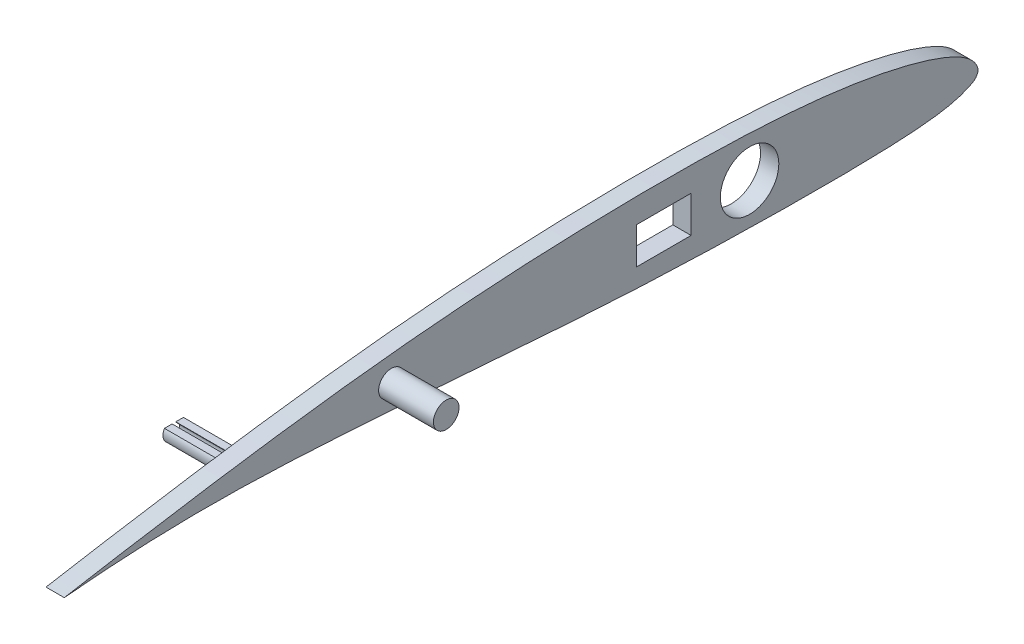
SolidWorks part; units mm, degrees
material "ABS generico"
ref_plane "Piano frontale" through (0, 0, 0) normal (0, 0, 1) x (1, 0, 0)
ref_plane "Piano superiore" through (0, 0, 0) normal (0, 1, 0) x (1, 0, 0)
ref_plane "Piano destro" through (0, 0, 0) normal (1, 0, 0) x (0, 0, -1)
curve "Curva1"
  spline degree 3 poles (0, 0.1724, 248.285) (0, -0.053, 250.4273) (0, 0.2462, 248.3284) (0, 0.5529, 246.6445) (0, 1.2459, 242.6221) (0, 2.0989, 237.7464) (0, 3.1818, 231.3634) (0, 4.2933, 223.9772) (0, 5.7312, 215.5604) (0, 7.1315, 206.3004) (0, 8.6324, 196.1631) (0, 10.1162, 185.3524) (0, 11.5493, 173.9891) (0, 12.8816, 162.1914) (0, 14.0593, 150.0724) (0, 15.0523, 137.7438) (0, 15.8256, 125.3116) (0, 16.3834, 112.8888) (0, 16.7267, 100.597) (0, 16.8648, 88.5669) (0, 16.792, 76.9314) (0, 16.4941, 65.8165) (0, 15.9609, 55.3329) (0, 15.1594, 45.573) (0, 14.0978, 36.6074) (0, 12.7884, 28.4972) (0, 11.2839, 21.2988) (0, 9.6413, 15.0749) (0, 7.9136, 9.8809) (0, 6.1182, 5.7699) (0, 4.2384, 2.7289) (0, 2.3057, 0.8126) (0, 0.7927, 0.0312) (0, -0.4105, -0.0213) (0, -1.7115, 0.4949) (0, -2.8658, 2.6253) (0, -4.0404, 5.6977) (0, -4.9287, 10.0719) (0, -5.5974, 15.6262) (0, -6.0122, 22.4122) (0, -6.265, 30.3619) (0, -6.3814, 39.3972) (0, -6.3554, 49.3987) (0, -6.2185, 60.2453) (0, -5.9476, 71.8018) (0, -5.5368, 83.9408) (0, -4.9386, 96.5461) (0, -4.1527, 109.5201) (0, -3.2196, 122.7671) (0, -2.1909, 136.1764) (0, -1.148, 149.6158) (0, -0.1602, 162.9314) (0, 0.706, 175.9537) (0, 1.3896, 188.4999) (0, 1.8332, 200.3712) (0, 1.9676, 211.3376) (0, 1.8232, 221.1842) (0, 1.4973, 229.6804) (0, 1.0741, 236.8065) (0, 0.6857, 242.1894) (0, 0.3087, 246.5181) (0, 0.1724, 248.285) (0, -0.053, 250.4273) (0, 0.2462, 248.3284) knots -0.014202 -0.006329 -0.001589 0 0.001576 0.006211 0.01368 0.023764 0.036307 0.051658 0.068045 0.086769 0.107053 0.128647 0.151303 0.174786 0.19886 0.223309 0.247929 0.272522 0.296848 0.320648 0.343669 0.365658 0.3864 0.405741 0.423561 0.439779 0.454311 0.467034 0.477831 0.486643 0.493542 0.498786 0.50271 0.50309 0.505896 0.510322 0.516831 0.525521 0.536535 0.549945 0.565696 0.583577 0.603379 0.624844 0.647727 0.671743 0.696673 0.722357 0.748609 0.77521 0.801891 0.828329 0.854175 0.879074 0.902636 0.924421 0.943939 0.960827 0.974827 0.985798 0.993671 0.998411 1 1.001576 1.006211 1.01368 periodic
sketch "Schizzo1" plane through (0, 0, 0) normal (1, 0, 0) x (0, 0, -1)
  line L0 (-250, 0) -> (0.0001, 0.0174) construction
  line L1 (0.0001, 0.0174) -> (-0.0034, 50.0174) construction
  line L2 (-62.4999, 16.3096) -> (-62.4999, -6.155) construction
  line L4 (-78.4999, 10.0773) -> (-93.4999, 10.0773)
  line L5 (-78.4999, 10.0773) -> (-78.4999, 0.0773)
  line L6 (-78.4999, 0.0773) -> (-93.4999, 0.0773)
  line L7 (-93.4999, 10.0773) -> (-93.4999, 0.0773)
  circle A0 centre (-62.4999, 5.0773) radius 8
  spline S0 degree 3 poles (-248.3284, 0.2462) (-250.4273, -0.053) (-248.285, 0.1724) (-246.5181, 0.3087) (-242.1894, 0.6857) (-236.8065, 1.0741) (-229.6804, 1.4973) (-221.1842, 1.8232) (-211.3376, 1.9676) (-200.3712, 1.8332) (-188.4999, 1.3896) (-175.9537, 0.706) (-162.9314, -0.1602) (-149.6158, -1.148) (-136.1764, -2.1909) (-122.7671, -3.2196) (-109.5201, -4.1527) (-96.5461, -4.9386) (-83.9408, -5.5368) (-71.8018, -5.9476) (-60.2453, -6.2185) (-49.3987, -6.3554) (-39.3972, -6.3814) (-30.3619, -6.265) (-22.4122, -6.0122) (-15.6262, -5.5974) (-10.0719, -4.9287) (-5.6977, -4.0404) (-2.6253, -2.8658) (-0.4949, -1.7115) (0.0213, -0.4105) (-0.0312, 0.7927) (-0.8126, 2.3057) (-2.7289, 4.2384) (-5.7699, 6.1182) (-9.8809, 7.9136) (-15.0749, 9.6413) (-21.2988, 11.2839) (-28.4972, 12.7884) (-36.6074, 14.0978) (-45.573, 15.1594) (-55.3329, 15.9609) (-65.8165, 16.4941) (-76.9314, 16.792) (-88.5669, 16.8648) (-100.597, 16.7267) (-112.8888, 16.3834) (-125.3116, 15.8256) (-137.7438, 15.0523) (-150.0724, 14.0593) (-162.1914, 12.8816) (-173.9891, 11.5493) (-185.3524, 10.1162) (-196.1631, 8.6324) (-206.3004, 7.1315) (-215.5604, 5.7312) (-223.9772, 4.2933) (-231.3634, 3.1818) (-237.7464, 2.0989) (-242.6221, 1.2459) (-246.6445, 0.5529) (-248.3284, 0.2462) (-250.4273, -0.053) (-248.285, 0.1724) knots -0.01368 -0.006211 -0.001576 0 0.001589 0.006329 0.014202 0.025173 0.039173 0.056061 0.075579 0.097364 0.120926 0.145825 0.171671 0.198109 0.22479 0.251391 0.277643 0.303327 0.328257 0.352273 0.375156 0.396621 0.416423 0.434304 0.450055 0.463465 0.474479 0.483169 0.489678 0.494104 0.49691 0.49729 0.501214 0.506458 0.513357 0.522169 0.532966 0.545689 0.560221 0.576439 0.594259 0.6136 0.634342 0.656331 0.679352 0.703152 0.727478 0.752071 0.776691 0.80114 0.825214 0.848697 0.871353 0.892947 0.913231 0.931955 0.948342 0.963693 0.976236 0.98632 0.993789 0.998424 1 1.001589 1.006329 1.014202 only from (-250, 0) to (-250, 0) construction
  spline S1 degree 3 poles (-248.3284, 0.2462) (-250.4273, -0.053) (-248.285, 0.1724) (-246.5181, 0.3087) (-242.1894, 0.6857) (-236.8065, 1.0741) (-229.6804, 1.4973) (-221.1842, 1.8232) (-211.3376, 1.9676) (-200.3712, 1.8332) (-188.4999, 1.3896) (-175.9537, 0.706) (-162.9314, -0.1602) (-149.6158, -1.148) (-136.1764, -2.1909) (-122.7671, -3.2196) (-109.5201, -4.1527) (-96.5461, -4.9386) (-83.9408, -5.5368) (-71.8018, -5.9476) (-60.2453, -6.2185) (-49.3987, -6.3554) (-39.3972, -6.3814) (-30.3619, -6.265) (-22.4122, -6.0122) (-15.6262, -5.5974) (-10.0719, -4.9287) (-5.6977, -4.0404) (-2.6253, -2.8658) (-0.4949, -1.7115) (0.0213, -0.4105) (-0.0312, 0.7927) (-0.8126, 2.3057) (-2.7289, 4.2384) (-5.7699, 6.1182) (-9.8809, 7.9136) (-15.0749, 9.6413) (-21.2988, 11.2839) (-28.4972, 12.7884) (-36.6074, 14.0978) (-45.573, 15.1594) (-55.3329, 15.9609) (-65.8165, 16.4941) (-76.9314, 16.792) (-88.5669, 16.8648) (-100.597, 16.7267) (-112.8888, 16.3834) (-125.3116, 15.8256) (-137.7438, 15.0523) (-150.0724, 14.0593) (-162.1914, 12.8816) (-173.9891, 11.5493) (-185.3524, 10.1162) (-196.1631, 8.6324) (-206.3004, 7.1315) (-215.5604, 5.7312) (-223.9772, 4.2933) (-231.3634, 3.1818) (-237.7464, 2.0989) (-242.6221, 1.2459) (-246.6445, 0.5529) (-248.3284, 0.2462) (-250.4273, -0.053) (-248.285, 0.1724) knots -0.01368 -0.006211 -0.001576 0 0.001589 0.006329 0.014202 0.025173 0.039173 0.056061 0.075579 0.097364 0.120926 0.145825 0.171671 0.198109 0.22479 0.251391 0.277643 0.303327 0.328257 0.352273 0.375156 0.396621 0.416423 0.434304 0.450055 0.463465 0.474479 0.483169 0.489678 0.494104 0.49691 0.49729 0.501214 0.506458 0.513357 0.522169 0.532966 0.545689 0.560221 0.576439 0.594259 0.6136 0.634342 0.656331 0.679352 0.703152 0.727478 0.752071 0.776691 0.80114 0.825214 0.848697 0.871353 0.892947 0.913231 0.931955 0.948342 0.963693 0.976236 0.98632 0.993789 0.998424 1 1.001589 1.006329 1.014202 only from (-250, 0) to (-250, 0)
  point P11 (-78.4999, 5.0773)
  dimension "D3" = 16
  dimension "D1" = 50
  dimension "D2" = 62.5
  dimension "D4" = 15
  dimension "D5" = 10
  dimension "D6" = 16
extrude "CorpoFoam" add sketch "Schizzo1" along normal blind 5
sketch "Schizzo2" plane through (0, 0, 0) normal (-1, 0, 0) x (0, 0, 1)
  circle A0 centre (160.4999, 6.0773) radius 3.5
  circle A1 centre (62.4999, 5.0773) radius 8 construction
  dimension "D1" = 7
  dimension "D2" = 98
  dimension "D3" = 1
extrude "PernoAggancio" add sketch "Schizzo2" against normal blind 20
sketch "Schizzo3" plane through (5, 0, 0) normal (1, 0, 0) x (0, 0, -1)
  line L0 (-200, 8.0593) -> (-200, 1.7757) construction
  line L1 (-200.5, 6.4175) -> (-199.5, 3.4175) construction
  line L2 (-197.4019, 6.4175) -> (-199.5, 6.4175)
  line L4 (-197.4019, 3.4175) -> (-199.5, 3.4175)
  line L7 (-200.5, 6.4175) -> (-200.5, 6.3317)
  line L9 (-199.5, 6.4175) -> (-199.5, 6.3317)
  line L10 (-199.5, 6.4175) -> (-200.5, 3.4175) construction
  line L11 (-200.5, 6.4175) -> (-202.5981, 6.4175)
  line L12 (-200.5, 3.4175) -> (-202.5981, 3.4175)
  line L13 (-199.5, 3.5033) -> (-199.5, 3.4175)
  line L14 (-200.5, 3.5033) -> (-200.5, 3.4175)
  arc A0 (-200.5, 6.3317) -> (-200.5, 3.5033) centre (-200, 4.9175) ccw
  arc A1 (-202.5981, 6.4175) -> (-202.5981, 3.4175) centre (-200, 4.9175) ccw
  arc A2 (-197.4019, 3.4175) -> (-197.4019, 6.4175) centre (-200, 4.9175) ccw
  arc A3 (-199.5, 3.5033) -> (-199.5, 6.3317) centre (-200, 4.9175) ccw
  spline S0 degree 3 poles (-248.3284, 0.2462) (-250.4273, -0.053) (-248.285, 0.1724) (-246.5181, 0.3087) (-242.1894, 0.6857) (-236.8065, 1.0741) (-229.6804, 1.4973) (-221.1842, 1.8232) (-211.3376, 1.9676) (-200.3712, 1.8332) (-188.4999, 1.3896) (-175.9537, 0.706) (-162.9314, -0.1602) (-149.6158, -1.148) (-136.1764, -2.1909) (-122.7671, -3.2196) (-109.5201, -4.1527) (-96.5461, -4.9386) (-83.9408, -5.5368) (-71.8018, -5.9476) (-60.2453, -6.2185) (-49.3987, -6.3554) (-39.3972, -6.3814) (-30.3619, -6.265) (-22.4122, -6.0122) (-15.6262, -5.5974) (-10.0719, -4.9287) (-5.6977, -4.0404) (-2.6253, -2.8658) (-0.4949, -1.7115) (0.0213, -0.4105) (-0.0312, 0.7927) (-0.8126, 2.3057) (-2.7289, 4.2384) (-5.7699, 6.1182) (-9.8809, 7.9136) (-15.0749, 9.6413) (-21.2988, 11.2839) (-28.4972, 12.7884) (-36.6074, 14.0978) (-45.573, 15.1594) (-55.3329, 15.9609) (-65.8165, 16.4941) (-76.9314, 16.792) (-88.5669, 16.8648) (-100.597, 16.7267) (-112.8888, 16.3834) (-125.3116, 15.8256) (-137.7438, 15.0523) (-150.0724, 14.0593) (-162.1914, 12.8816) (-173.9891, 11.5493) (-185.3524, 10.1162) (-196.1631, 8.6324) (-206.3004, 7.1315) (-215.5604, 5.7312) (-223.9772, 4.2933) (-231.3634, 3.1818) (-237.7464, 2.0989) (-242.6221, 1.2459) (-246.6445, 0.5529) (-248.3284, 0.2462) (-250.4273, -0.053) (-248.285, 0.1724) knots -0.01368 -0.006211 -0.001576 0 0.001589 0.006329 0.014202 0.025173 0.039173 0.056061 0.075579 0.097364 0.120926 0.145825 0.171671 0.198109 0.22479 0.251391 0.277643 0.303327 0.328257 0.352273 0.375156 0.396621 0.416423 0.434304 0.450055 0.463465 0.474479 0.483169 0.489678 0.494104 0.49691 0.49729 0.501214 0.506458 0.513357 0.522169 0.532966 0.545689 0.560221 0.576439 0.594259 0.6136 0.634342 0.656331 0.679352 0.703152 0.727478 0.752071 0.776691 0.80114 0.825214 0.848697 0.871353 0.892947 0.913231 0.931955 0.948342 0.963693 0.976236 0.98632 0.993789 0.998424 1 1.001589 1.006329 1.014202 only from (-250, 0) to (-250, 0) construction
  dimension "D1" = 3
  dimension "D2" = 6
  dimension "D3" = 50
  dimension "D4" = 1
extrude "PernoAggancioAlettone" add sketch "Schizzo3" against normal blind 20
